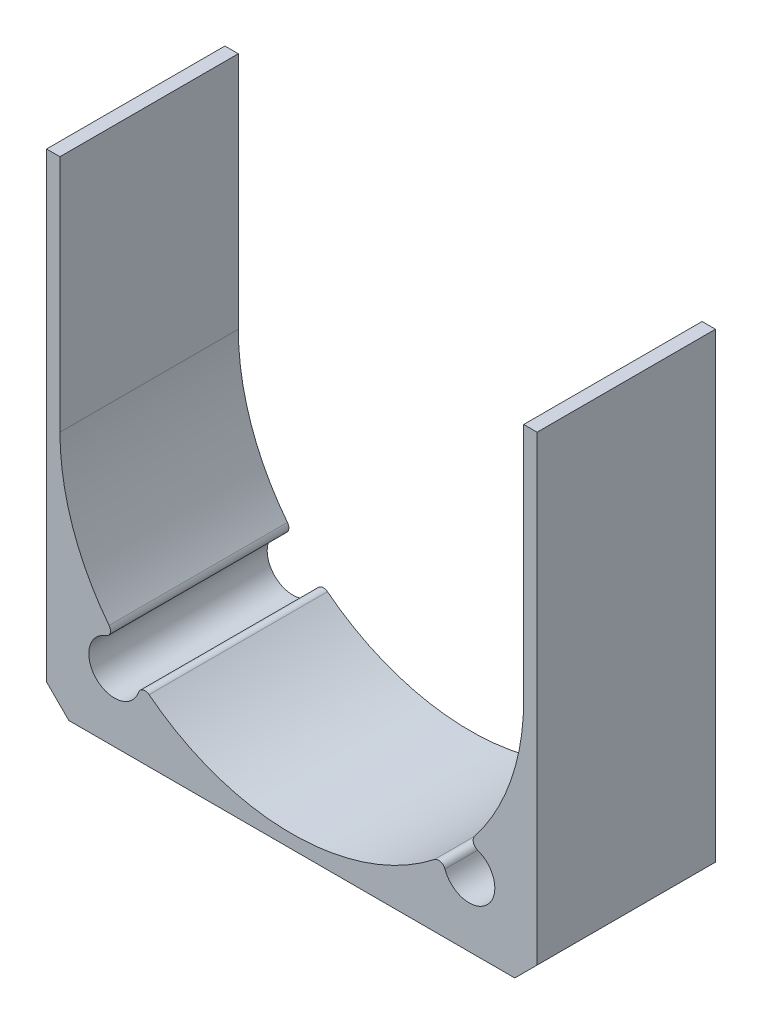
SolidWorks part; units mm, degrees
ref_plane "Front Plane" through (0, 0, 0) normal (0, 0, 1) x (1, 0, 0)
ref_plane "Top Plane" through (0, 0, 0) normal (0, 1, 0) x (1, 0, 0)
ref_plane "Right Plane" through (0, 0, 0) normal (1, 0, 0) x (0, 0, -1)
sketch "Sketch1" plane through (0, 0, 0) normal (0, 0, 1) x (1, 0, 0)
  line L0 (-104, 0) -> (-104, 110)
  line L1 (110, 110) -> (104, 110)
  line L2 (110, 110) -> (110, -110)
  line L3 (110, -110) -> (-110, -110)
  line L4 (-110, 110) -> (-110, -110)
  line L5 (110, 110) -> (-110, -110) construction
  line L6 (110, -110) -> (-110, 110) construction
  line L7 (104, 0) -> (104, 110)
  line L8 (-104, 110) -> (-110, 110)
  circle A0 centre (0, 0) radius 100 construction
  arc A1 (-104, 0) -> (104, 0) centre (0, 0) ccw
  circle A2 centre (0, 0) radius 104 construction
  dimension "D1" = 200
  dimension "D2" = 220
  dimension "D3" = 4
extrude "Boss-Extrude1" add sketch "Sketch1" along normal blind 80
sketch "Sketch3" plane through (0, 0, 80) normal (0, 0, 1) x (1, 0, 0)
  line L1 (79.5495, 79.5495) -> (-79.5495, 79.5495) construction
  line L2 (79.5495, 79.5495) -> (79.5495, -79.5495) construction
  line L3 (79.5495, -79.5495) -> (-79.5495, -79.5495) construction
  line L4 (-79.5495, 79.5495) -> (-79.5495, -79.5495) construction
  line L5 (79.5495, 79.5495) -> (-79.5495, -79.5495) construction
  line L6 (79.5495, -79.5495) -> (-79.5495, 79.5495) construction
  circle A0 centre (-79.5495, -79.5495) radius 11.5
  circle A1 centre (79.5495, -79.5495) radius 11.5
  arc A5 (-104, 0) -> (104, 0) centre (0, 0) ccw construction
  point P4 (0, 0)
  point P5 (0, 0)
  dimension "D1" = 23
  dimension "D2" = 3
extrude "Cut-Extrude1" cut sketch "Sketch3" against normal through all
fillet "Fillet1" radius 3 4 edges at (78.6134, -68.0877, 40) (68.0877, -78.6134, 40) (-68.0877, -78.6134, 40) (-78.6134, -68.0877, 40)
chamfer "Chamfer1" distance 10 angle 45 2 edges at (110, -110, 40) (-110, -110, 40)
sketch "Sketch4" plane through (0, 0, 80) normal (0, 0, 1) x (1, 0, 0)
  line L0 (110, -100) -> (110, 110) construction
  line L1 (-110, 110) -> (110, 110)
  line L2 (-110, 110) -> (-110, 107)
  line L3 (-110, 107) -> (110, 107)
  line L4 (110, 110) -> (110, 107)
  dimension "D1" = 3
extrude "Cut-Extrude2" cut sketch "Sketch4" against normal through all
